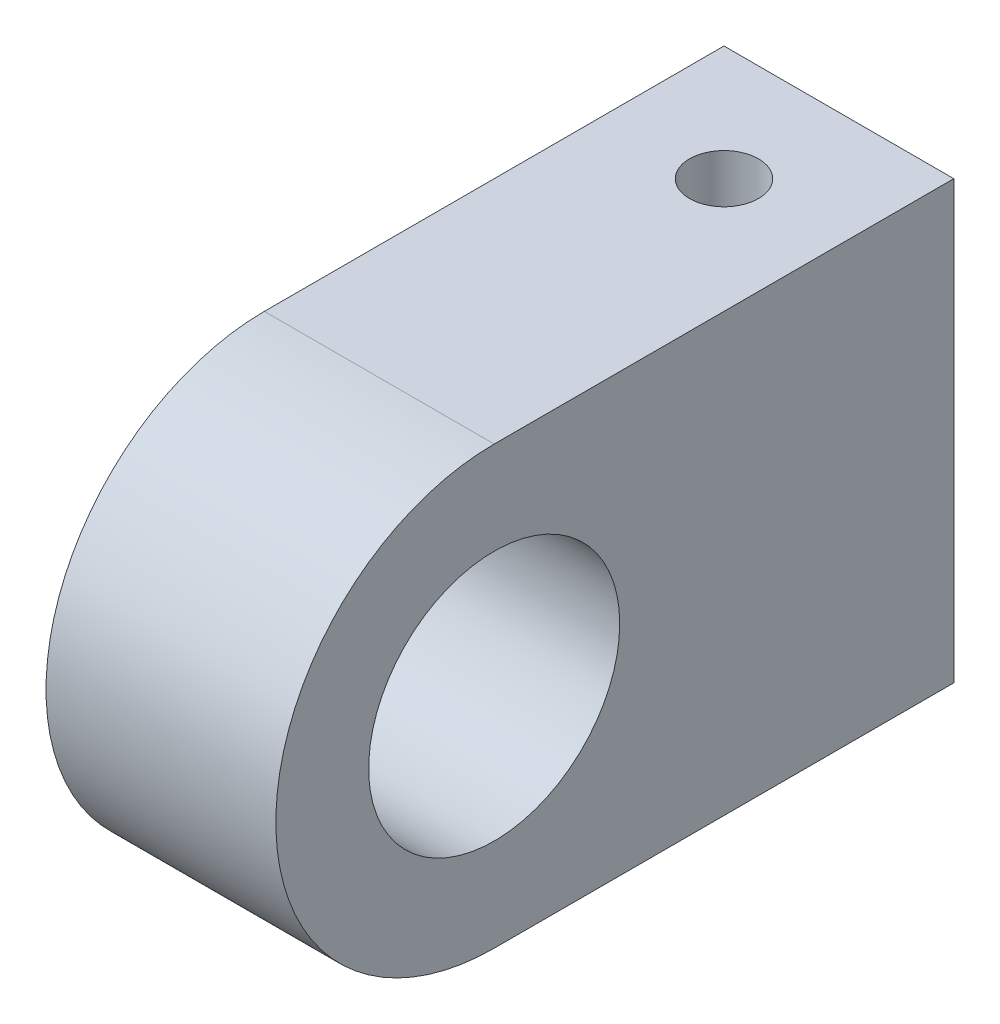
SolidWorks part; units mm, degrees
ref_plane "前视基准面" through (0, 0, 0) normal (0, 0, 1) x (1, 0, 0)
ref_plane "上视基准面" through (0, 0, 0) normal (0, 1, 0) x (1, 0, 0)
ref_plane "右视基准面" through (0, 0, 0) normal (1, 0, 0) x (0, 0, -1)
sketch "草图1" plane through (0, 0, 0) normal (1, 0, 0) x (0, 0, -1)
  line L0 (0, 9.5) -> (20, 9.5)
  line L1 (20, 9.5) -> (20, -9.5)
  line L2 (20, -9.5) -> (0, -9.5)
  circle A0 centre (0, 0) radius 5.4628
  arc A1 (-9.5, 0) -> (0, 9.5) centre (0, 0) cw
  arc A2 (-9.5, 0) -> (0, -9.5) centre (0, 0) ccw
  dimension "D1" = 20
  dimension "D2" = 9.5
extrude "凸台-拉伸1" add sketch "草图1" along normal blind 10
sketch "草图2" plane through (0, 9.5, 0) normal (0, 1, 0) x (1, 0, 0)
  line L0 (0, 20) -> (10, 10) construction
  line L1 (0, 20) -> (0, 0) construction
  line L2 (10, 20) -> (10, 0) construction
  circle A0 centre (5, 15) radius 1.5
extrude "切除-拉伸1" cut sketch "草图2" against normal through all
sketch "草图3" plane through (10, 0, 0) normal (1, 0, 0) x (0, 0, -1)
  line L0 (20, -9.5) -> (20, 9.5) construction
  point P0 (20, 0)
